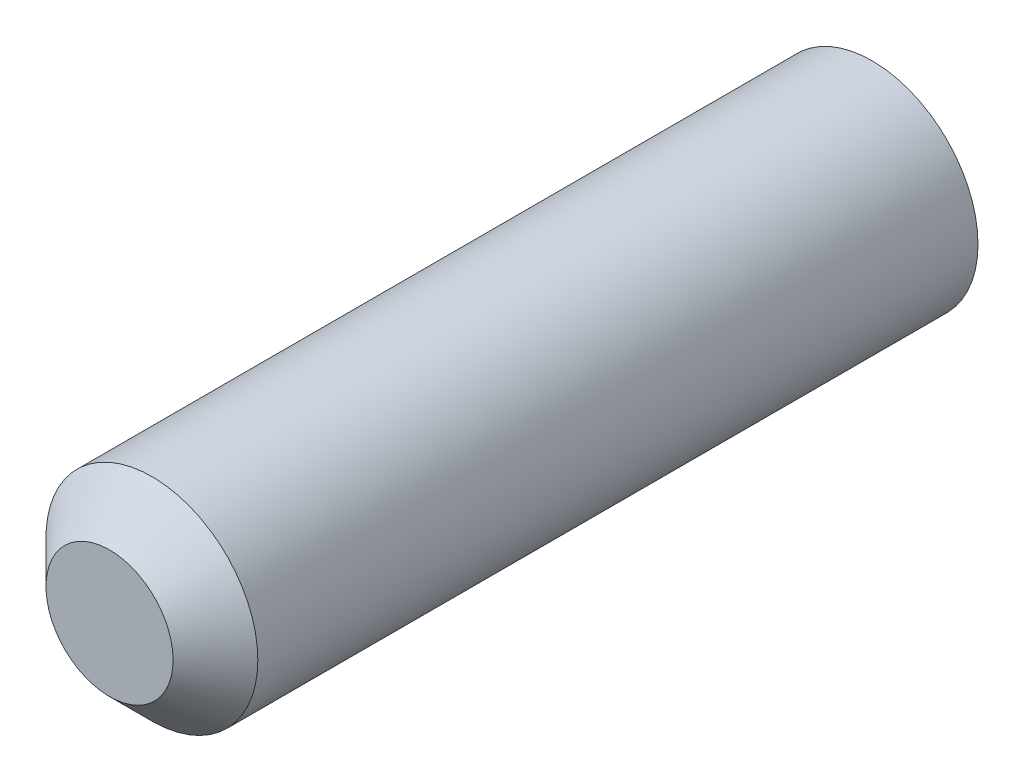
SolidWorks part; units mm, degrees
material "6061 Alloy"
ref_plane "Front Plane" through (0, 0, 0) normal (0, 0, 1) x (1, 0, 0)
ref_plane "Top Plane" through (0, 0, 0) normal (0, 1, 0) x (1, 0, 0)
ref_plane "Right Plane" through (0, 0, 0) normal (1, 0, 0) x (0, 0, -1)
sketch "Sketch1" plane through (0, 0, 0) normal (0, 0, 1) x (1, 0, 0)
  circle A0 centre (0, 0) radius 6.35
  dimension "D1" = 12.7
extrude "Boss-Extrude1" add sketch "Sketch1" along normal mid plane 45.72
chamfer "Chamfer1" distance 2.54 angle 45 1 edges at (6.35, 0, 22.86)
sketch "Sketch2" plane through (0, 0, -22.86) normal (0, 0, -1) x (-1, 0, 0)
  circle A0 centre (0, 0) radius 1.9812
  dimension "D1" = 3.9624
extrude "Cut-Extrude1" cut sketch "Sketch2" against normal blind 14.2748
